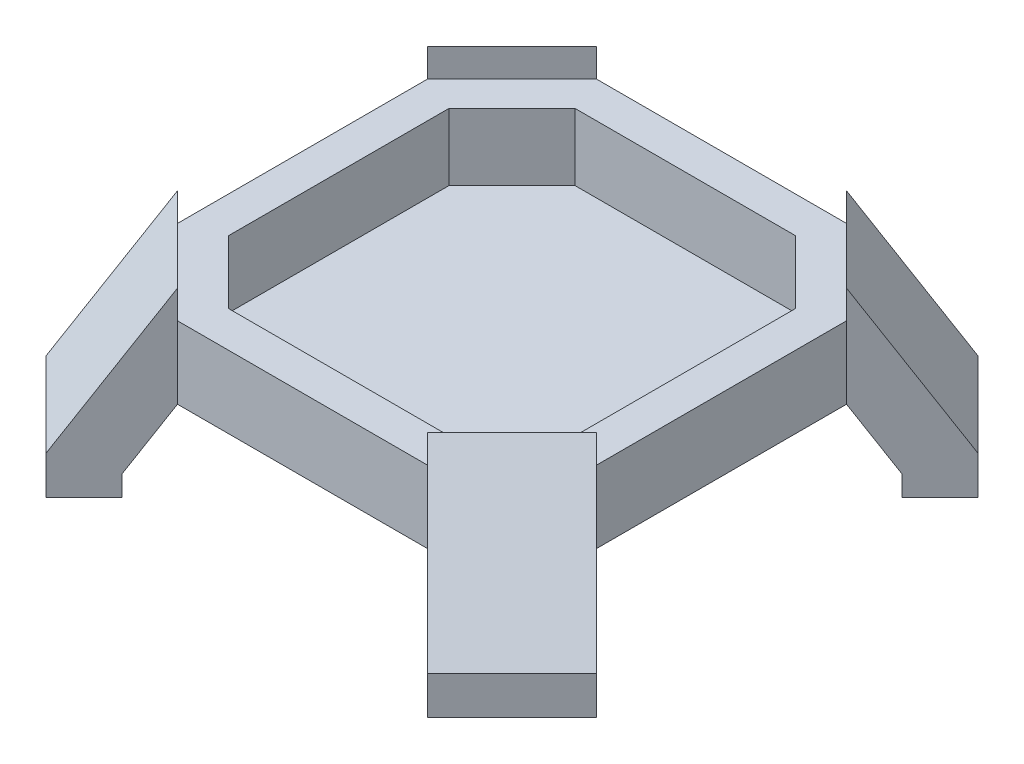
SolidWorks part; units mm, degrees
ref_plane "Front Plane" through (0, 0, 0) normal (0, 0, 1) x (1, 0, 0)
ref_plane "Top Plane" through (0, 0, 0) normal (0, 1, 0) x (1, 0, 0)
ref_plane "Right Plane" through (0, 0, 0) normal (1, 0, 0) x (0, 0, -1)
sketch "Sketch1" plane through (0, 0, 0) normal (0, 1, 0) x (1, 0, 0)
  line L0 (24.8945, 77.3376) -> (48.2291, 54.003)
  line L1 (-44.3409, 77.3376) -> (24.8945, 77.3376)
  line L2 (-67.6754, 54.003) -> (-67.6754, -15.2324)
  line L3 (-44.3409, -38.5669) -> (24.8945, -38.5669)
  line L4 (48.2291, 54.003) -> (48.2291, -15.2324)
  line L5 (-55.8341, -3.391) -> (-67.6754, -15.2324) construction
  line L6 (-44.3409, -38.5669) -> (-67.6754, -15.2324) construction
  line L7 (-67.6754, 54.003) -> (-44.3409, 77.3376)
  line L8 (-67.6754, -15.2324) -> (-44.3409, -38.5669)
  line L9 (48.2291, -15.2324) -> (24.8945, -38.5669)
  line L10 (-44.3409, 77.3376) -> (-67.6754, 54.003) construction
  line L11 (-32.4996, 65.4962) -> (-44.3409, 77.3376) construction
  line L12 (24.8945, 77.3376) -> (48.2291, 54.003) construction
  point P0 (0, 0)
  point P1 (83.0623, -50.0656)
  point P2 (59.7277, -73.4001)
  point P3 (-50.0656, -73.4001)
  point P4 (-73.4001, -50.0656)
  point P16 (-73.4001, 59.7277)
  point P18 (-50.0656, 83.0623)
  point P21 (0, 0)
  point P22 (0, 0)
  point P23 (0, 0)
  point P24 (73.4001, 62.6422)
  point P25 (0, 0)
  point P26 (0, 0)
  point P27 (0, 0)
  point P28 (0, 0)
  point P29 (73.4001, 41.3502)
  point P30 (0, 0)
  point P31 (83.0623, 59.7277)
  point P33 (59.7277, 83.0623)
  point P36 (42.875, -93.9963)
extrude "Boss-Extrude1" add sketch "Sketch1" along normal blind 20
shell "Shell1" thickness 10
sketch "Sketch2" plane through (0, 1.5, 0) normal (0, 1, 0) x (1, 0, 0)
  line L1 (-28.8102, 73.0253) -> (41.1898, 73.0253)
  line L2 (-28.8102, 73.0253) -> (-28.8102, -6.9747)
  line L3 (-28.8102, -6.9747) -> (41.1898, -6.9747)
  line L4 (41.1898, 73.0253) -> (41.1898, -6.9747)
  line L5 (-28.8102, 73.0253) -> (41.1898, -6.9747) construction
  line L6 (-28.8102, -6.9747) -> (41.1898, 73.0253) construction
  point P0 (6.1898, 33.0253)
  point P5 (6.1898, 33.0253)
  dimension "D1" = 70
  dimension "D2" = 80
ref_plane "Plane1" through (-6.8362, 0, 6.8362) normal (0.7071, 0, -0.7071) x (0, -1, 0)
sketch "Sketch3" plane through (-6.8362, 0, 6.8362) normal (0.7071, 0, -0.7071) x (0, -1, 0)
  line L0 (-27.8247, 86.0397) -> (11.738, 111.7695)
  line L2 (22.3031, 111.7695) -> (22.3031, 96.9274)
  line L3 (22.3031, 96.9274) -> (16.7412, 96.9274)
  line L4 (16.7412, 96.9274) -> (0, 86.0397)
  line L5 (0, 86.0397) -> (-27.8247, 86.0397)
  line L6 (-53.574, 69.2935) -> (-27.8247, 86.0397) construction
  line L8 (11.738, 111.7695) -> (22.3031, 111.7695)
  point P3 (17.7048, 97.5541)
  point P4 (9.088, 110.046)
  point P9 (25.8325, 116.9418)
  point P10 (0, 0)
  point P11 (5.1519, 107.4861)
  point P12 (22.3031, 111.7695)
  point P13 (16.7412, 96.9274)
extrude "Boss-Extrude2" add sketch "Sketch3" along normal blind 33
ref_plane "Plane2" through (0, 0, -19.3853) normal (0, 0, 1) x (1, 0, 0)
mirror "Mirror1" about plane through (0, 0, -19.3853) normal (0, 0, 1) of "Boss-Extrude2"
ref_plane "Plane3" through (-9.7232, 0, 0) normal (-1, 0, 0) x (0, 0, 1)
mirror "Mirror2" about plane through (-9.7232, 0, 0) normal (-1, 0, 0) of "Mirror1", "Boss-Extrude2"
